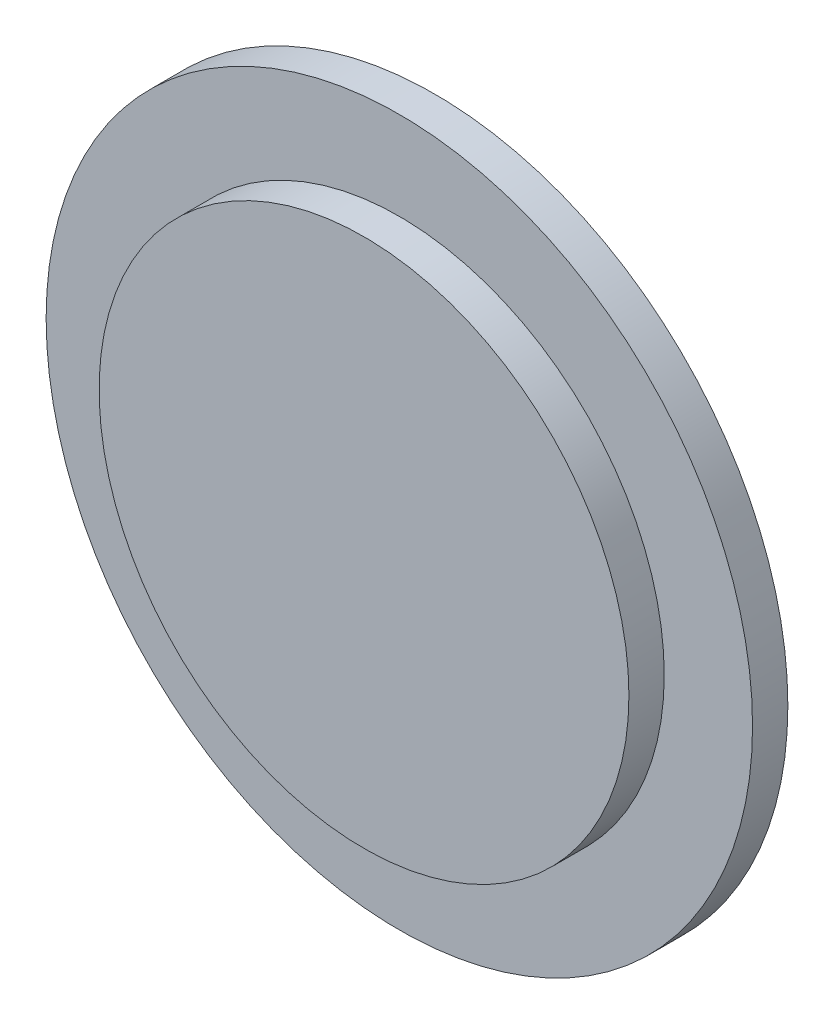
SolidWorks part; units mm, degrees
ref_plane "Front Plane" through (0, 0, 0) normal (0, 0, 1) x (1, 0, 0)
ref_plane "Top Plane" through (0, 0, 0) normal (0, 1, 0) x (1, 0, 0)
ref_plane "Right Plane" through (0, 0, 0) normal (1, 0, 0) x (0, 0, -1)
sketch "Sketch1" plane through (0, 0, 0) normal (0, 0, 1) x (1, 0, 0)
  circle A0 centre (0, 0) radius 7.5
  dimension "D1" = 15
extrude "Boss-Extrude1" add sketch "Sketch1" along normal mid plane 3
sketch "Sketch2" plane through (0, 0, 0) normal (0, 0, 1) x (1, 0, 0)
  circle A0 centre (0, 0) radius 10
  dimension "D1" = 20
extrude "Boss-Extrude2" add sketch "Sketch2" along normal mid plane 1
